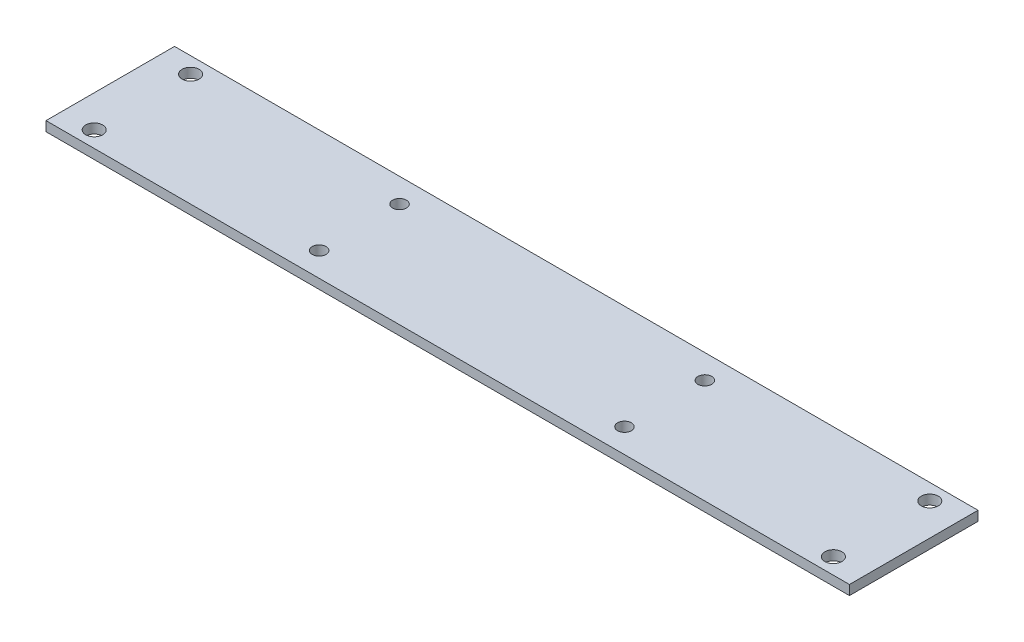
SolidWorks part; units mm, degrees
ref_plane "前视基准面" through (0, 0, 0) normal (0, 0, 1) x (1, 0, 0)
ref_plane "上视基准面" through (0, 0, 0) normal (0, 1, 0) x (1, 0, 0)
ref_plane "右视基准面" through (0, 0, 0) normal (1, 0, 0) x (0, 0, -1)
sketch "草图1" plane through (0, 0, 0) normal (0, 1, 0) x (1, 0, 0)
  line L0 (0, 20) -> (0, -20) construction
  line L1 (-125, 20) -> (125, 20)
  line L2 (-125, 20) -> (-125, -20)
  line L3 (-125, -20) -> (125, -20)
  line L4 (125, 20) -> (125, -20)
  line L5 (-125, 20) -> (125, -20) construction
  line L6 (-125, -20) -> (125, 20) construction
  line L7 (-125, 0) -> (125, 0) construction
  circle A0 centre (-47.5, 12.5) radius 2.15
  circle A1 centre (47.5, 12.5) radius 2.15
  circle A2 centre (47.5, -12.5) radius 2.15
  circle A3 centre (-47.5, -12.5) radius 2.15
  circle A4 centre (-115, 15) radius 2.65
  circle A5 centre (115, 15) radius 2.65
  circle A6 centre (-115, -15) radius 2.65
  circle A7 centre (115, -15) radius 2.65
  point P0 (0, 0)
  dimension "D5" = 4.3
  dimension "D6" = 5.3
  dimension "D1" = 250
  dimension "D2" = 40
  dimension "D3" = 95
  dimension "D4" = 25
  dimension "D7" = 10
  dimension "D8" = 5
extrude "凸台-拉伸1" add sketch "草图1" along normal blind 3
